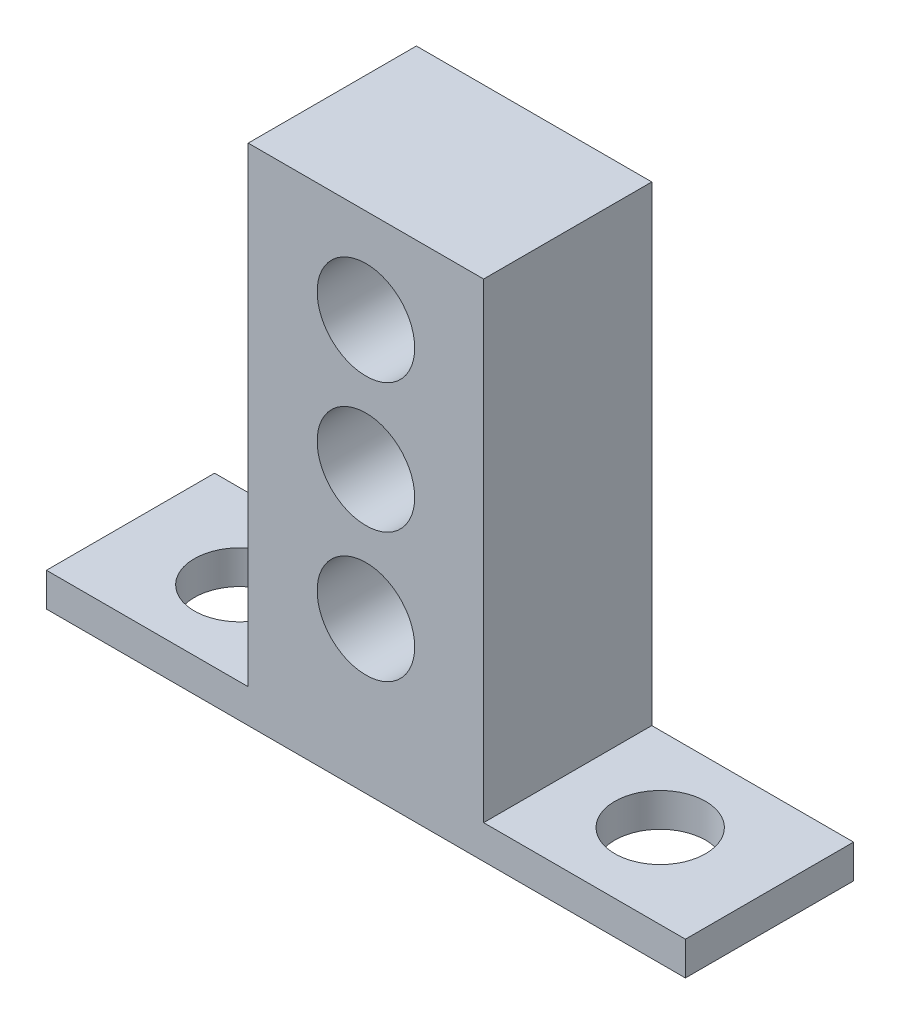
SolidWorks part; units mm, degrees
ref_plane "Front Plane" through (0, 0, 0) normal (0, 0, 1) x (1, 0, 0)
ref_plane "Top Plane" through (0, 0, 0) normal (0, 1, 0) x (1, 0, 0)
ref_plane "Right Plane" through (0, 0, 0) normal (1, 0, 0) x (0, 0, -1)
sketch "Sketch1" plane through (0, 0, 0) normal (0, 0, 1) x (1, 0, 0)
  line L0 (8.89, 30.988) -> (0, 30.988) construction
  line L1 (0, 0) -> (17.78, 0)
  line L2 (0, 0) -> (0, 38.1)
  line L3 (0, 38.1) -> (17.78, 38.1)
  line L4 (17.78, 0) -> (17.78, 38.1)
  line L5 (8.89, 21.209) -> (0, 21.209) construction
  line L6 (8.89, 11.43) -> (0, 11.43) construction
  line L7 (8.89, 11.43) -> (8.89, 21.209) construction
  line L8 (8.89, 11.43) -> (8.89, 0) construction
  line L9 (8.89, 21.209) -> (8.89, 30.988) construction
  circle A0 centre (8.89, 30.988) radius 3.683
  circle A1 centre (8.89, 21.209) radius 3.683
  circle A2 centre (8.89, 11.43) radius 3.683
  dimension "D2" = 7.366
  dimension "D1" = 38.1
  dimension "D3" = 17.78
  dimension "D4" = 8.89
  dimension "D5" = 9.779
  dimension "D6" = 11.43
  dimension "D7" = 9.779
extrude "Boss-Extrude1" add sketch "Sketch1" along normal blind 12.7
sketch "Sketch2" plane through (17.78, 0, 0) normal (1, 0, 0) x (0, 0, -1)
  line L0 (0, 0) -> (0, 38.1) construction
  line L1 (-12.7, 0) -> (0, 0)
  line L2 (-12.7, 0) -> (-12.7, 2.54)
  line L3 (-12.7, 2.54) -> (0, 2.54)
  line L4 (0, 0) -> (0, 2.54)
  dimension "D1" = 2.54
extrude "Boss-Extrude2" add sketch "Sketch2" along normal blind 15.24
sketch "Sketch3" plane through (0, 0, 0) normal (-1, 0, 0) x (0, 0, 1)
  line L0 (0, 38.1) -> (0, 0) construction
  line L1 (12.7, 0) -> (0, 0)
  line L2 (12.7, 0) -> (12.7, 2.54)
  line L3 (12.7, 2.54) -> (0, 2.54)
  line L4 (0, 0) -> (0, 2.54)
  dimension "D1" = 2.54
extrude "Boss-Extrude3" add sketch "Sketch3" along normal blind 15.24
sketch "Sketch4" plane through (0, 0, 0) normal (0, -1, 0) x (1, 0, 0)
  line L0 (-6.985, 6.35) -> (24.765, 6.35) construction
  line L1 (8.89, 12.7) -> (-6.985, 6.35) construction
  line L2 (-15.24, 12.7) -> (33.02, 12.7) construction
  line L3 (8.89, 12.7) -> (24.765, 6.35) construction
  line L4 (33.02, 6.35) -> (24.765, 6.35) construction
  line L5 (33.02, 12.7) -> (33.02, 0) construction
  circle A0 centre (-6.985, 6.35) radius 3.429
  circle A1 centre (24.765, 6.35) radius 3.429
  dimension "D2" = 6.858
  dimension "D1" = 31.75
extrude "Cut-Extrude1" cut sketch "Sketch4" against normal through all
